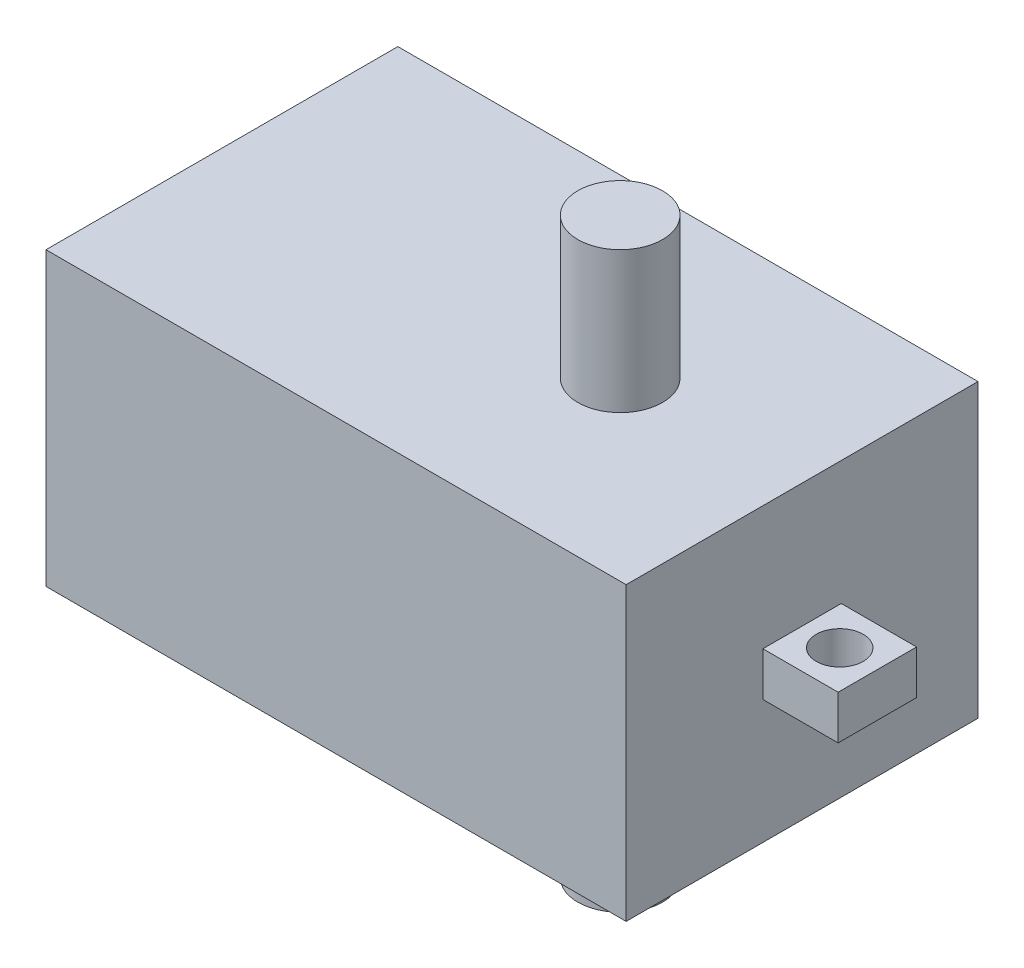
SolidWorks part; units mm, degrees
ref_plane "Front Plane" through (0, 0, 0) normal (0, 0, 1) x (1, 0, 0)
ref_plane "Top Plane" through (0, 0, 0) normal (0, 1, 0) x (1, 0, 0)
ref_plane "Right Plane" through (0, 0, 0) normal (1, 0, 0) x (0, 0, -1)
sketch "Sketch1" plane through (0, 0, 0) normal (0, 0, 1) x (1, 0, 0)
  line L1 (18.5, -9.3) -> (-18.5, -9.3)
  line L2 (18.5, -9.3) -> (18.5, 9.3)
  line L3 (18.5, 9.3) -> (-18.5, 9.3)
  line L4 (-18.5, -9.3) -> (-18.5, 9.3)
  line L5 (18.5, -9.3) -> (-18.5, 9.3) construction
  line L6 (18.5, 9.3) -> (-18.5, -9.3) construction
  point P0 (0, 0)
  dimension "D1" = 18.6
  dimension "D2" = 37
extrude "Boss-Extrude1" add sketch "Sketch1" along normal blind 22.44
sketch "Sketch6" plane through (18.5, 0, 0) normal (1, 0, 0) x (0, 0, -1)
  line L0 (-22.44, 9.3) -> (0, -9.3) construction
  line L1 (0, 9.3) -> (-22.44, -9.3) construction
  line L3 (-8.72, -1.4) -> (-13.72, -1.4)
  line L4 (-8.72, -1.4) -> (-8.72, 1.4)
  line L5 (-8.72, 1.4) -> (-13.72, 1.4)
  line L6 (-13.72, -1.4) -> (-13.72, 1.4)
  line L7 (-8.72, -1.4) -> (-13.72, 1.4) construction
  line L8 (-8.72, 1.4) -> (-13.72, -1.4) construction
  point P8 (-11.22, 0)
  dimension "D1" = 2.8
  dimension "D2" = 5
extrude "Boss-Extrude2" add sketch "Sketch6" along normal blind 4.8
sketch "Sketch7" plane through (0, 1.4, 0) normal (0, 1, 0) x (1, 0, 0)
  line L0 (18.5, -8.72) -> (23.3, -13.72) construction
  line L1 (23.3, -13.72) -> (18.5, -13.72) construction
  line L2 (23.3, -8.72) -> (23.3, -13.72) construction
  line L3 (23.3, -8.72) -> (18.5, -13.72) construction
  circle A0 centre (20.9, -11.22) radius 1.5
extrude "Cut-Extrude1" cut sketch "Sketch7" against normal up to next
sketch "Sketch8" plane through (0, 9.3, 0) normal (0, 1, 0) x (1, 0, 0)
  line L0 (20.9, -11.22) -> (6.9, -11.22) construction
  circle A1 centre (6.9, -11.22) radius 2.7
  point P1 (20.9, -11.22)
  dimension "D1" = 14
extrude "Boss-Extrude3" add sketch "Sketch8" along normal blind 9
ref_plane "Plane3" through (0, 0, 0) normal (0, 1, 0) x (1, 0, 0)
mirror "Mirror1" about plane through (0, 0, 0) normal (0, 1, 0) of "Boss-Extrude3"
